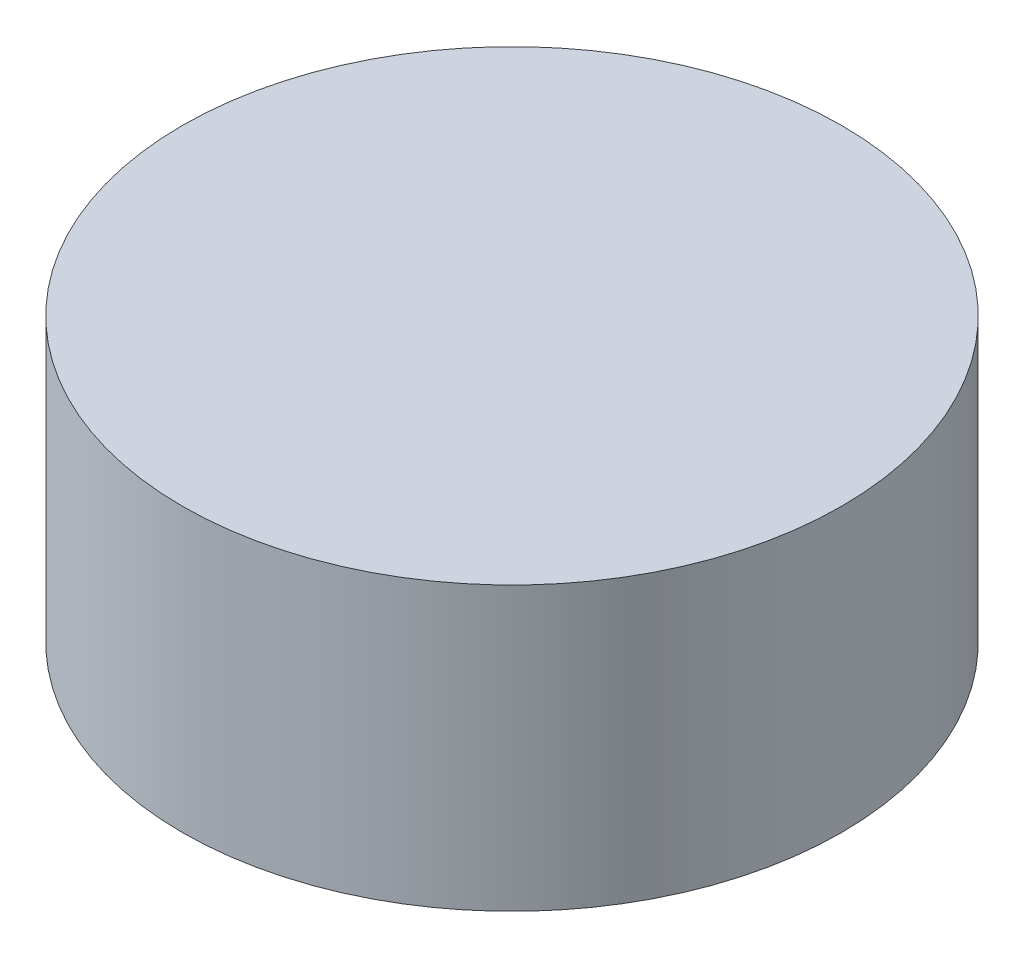
SolidWorks part; units mm, degrees
ref_plane "Front Plane" through (0, 0, 0) normal (0, 0, 1) x (1, 0, 0)
ref_plane "Top Plane" through (0, 0, 0) normal (0, 1, 0) x (1, 0, 0)
ref_plane "Right Plane" through (0, 0, 0) normal (1, 0, 0) x (0, 0, -1)
sketch "Sketch1" plane through (0, 0, 0) normal (0, 1, 0) x (1, 0, 0)
  circle A0 centre (0, 0) radius 35
extrude "Boss-Extrude1" add sketch "Sketch1" against normal blind 30
